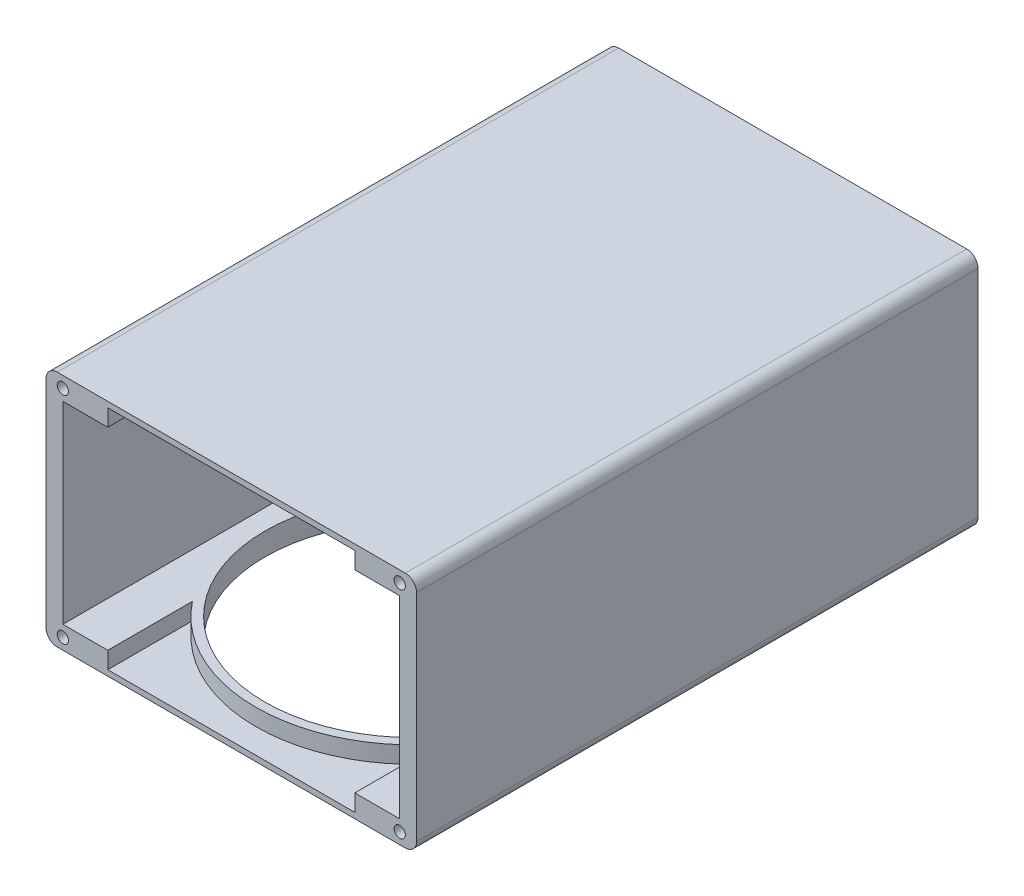
SolidWorks part; units mm, degrees
ref_plane "Front Plane" through (0, 0, 0) normal (0, 0, 1) x (1, 0, 0)
ref_plane "Top Plane" through (0, 0, 0) normal (0, 1, 0) x (1, 0, 0)
ref_plane "Right Plane" through (0, 0, 0) normal (1, 0, 0) x (0, 0, -1)
other "Configuration Table"
sketch "Sketch1" plane through (0, 0, 0) normal (0, 1, 0) x (1, 0, 0)
  line L1 (0, 0) -> (150, 0)
  line L2 (0, 0) -> (0, 160)
  line L3 (0, 160) -> (150, 160)
  line L4 (150, 0) -> (150, 160)
  dimension "D1" = 150
  dimension "D2" = 160
sketch "Sketch4" plane through (0, 0, 0) normal (0, 0, 1) x (1, 0, 0)
  line L0 (130, 86) -> (150, 86)
  line L1 (0, 0) -> (150, 0)
  line L2 (0, 0) -> (0, 86)
  line L3 (0, 86) -> (150, 86)
  line L4 (150, 0) -> (150, 86)
  line L5 (130, 93.5) -> (130, 86)
  line L6 (0, 0) -> (0, 20)
  line L7 (130, 25) -> (110, 25)
  line L8 (130, 25) -> (130, 50)
  line L9 (130, 50) -> (110, 50)
  line L10 (110, 25) -> (110, 50)
  line L11 (0, 20) -> (-5, 20)
  line L14 (20, -7.5) -> (20, 0)
  line L15 (20, 0) -> (0, 0)
  line L22 (0, 43) -> (150, 43) construction
  line L23 (75, 86) -> (75, 0) construction
  line L24 (20, 86) -> (0, 86)
  line L25 (20, 93.5) -> (20, 86)
  line L28 (0, 66) -> (-5, 66)
  line L29 (0, 86) -> (0, 66)
  line L32 (150, 66) -> (155, 66)
  line L33 (150, 86) -> (150, 66)
  line L34 (130, 0) -> (150, 0)
  line L35 (130, -7.5) -> (130, 0)
  line L38 (150, 20) -> (155, 20)
  line L39 (150, 0) -> (150, 20)
  line L40 (0, 86) -> (20, 86)
  line L41 (-7.5, -10) -> (-7.5, 0)
  line L43 (-7.5, 96) -> (157.5, 96)
  line L45 (157.5, -10) -> (-7.5, -10)
  line L46 (-5, 66) -> (-7.5, 66)
  line L47 (-5, 20) -> (-7.5, 20)
  line L48 (104.8793, 0) -> (-104.8793, 0) construction
  line L49 (20, -7.5) -> (130, -7.5)
  line L50 (155, 20) -> (157.5, 20)
  line L51 (0, 66) -> (0, 86)
  line L52 (155, 66) -> (157.5, 66)
  line L53 (20, 93.5) -> (130, 93.5)
  line L54 (-7.5, 66) -> (-7.5, 96)
  line L55 (157.5, 66) -> (157.5, 96)
  line L56 (157.5, 20) -> (157.5, -10)
  line L57 (-7.5, 20) -> (-7.5, 0)
  line L58 (130, 86) -> (150, 86)
  line L59 (150, 20) -> (150, 0)
  line L60 (0, 20) -> (0, 0)
  point P18 (0, 43)
  dimension "D1" = 150
  dimension "D2" = 86
  dimension "D5" = 25
  dimension "D6" = 20
  dimension "D7" = 20
  dimension "D8" = 5
  dimension "D11" = 106
  dimension "D12" = 165
sketch "Sketch5" plane through (0, 0, 0) normal (1, 0, 0) x (0, 0, -1)
  line L1 (0, 0) -> (160, 0)
  line L2 (0, 0) -> (0, 86)
  line L3 (0, 86) -> (160, 86)
  line L4 (160, 0) -> (160, 86)
  dimension "D1" = 160
  dimension "D2" = 86
extrude "Boss-Extrude3" add sketch "Sketch4" against normal blind 250 contours L52 L55 L43 L54 L46 L28 L2 L3 L25 L53 L5 L0 L4 L32 | L47 L57 L41 L45 L56 L50 L38 L4 L1 L35 L49 L14 L2 L11
fillet "Fillet1" radius 5 2 edges at (-7.5, 96, -125) (157.5, 96, -125)
fillet "Fillet2" radius 5 2 edges at (-7.5, -10, -125) (157.5, -10, -125)
sketch "Sketch7" plane through (0, 0, 0) normal (0, -1, 0) x (-1, 0, 0)
  line L0 (-150, 160) -> (-75, 160) construction
  line L1 (-150, 160) -> (0, 160) construction
  line L2 (-75, 160) -> (-75, 81) construction
  circle A0 centre (-75, 81) radius 66
  dimension "D2" = 132
  dimension "D1" = 79
extrude "Cut-Extrude1" cut sketch "Sketch7" along normal blind 10 contours A0
sketch "Sketch9" plane through (0, 0, 0) normal (0, -1, 0) x (1, 0, 0)
  line L0 (9, -81) -> (75, -81) construction
  circle A0 centre (75, -81) radius 66 construction
  circle A1 centre (75, -81) radius 70
  circle A2 centre (75, -81) radius 66
  dimension "D1" = 140
extrude "Boss-Extrude4" add sketch "Sketch9" along normal blind 8
sketch "Sketch14" plane through (0, 0, -250) normal (0, 0, -1) x (-1, 0, 0)
  line L0 (0, 86) -> (0, 91) construction
  line L1 (0, 106.7771) -> (0, -106.7771) construction
  line L2 (-150, 86) -> (-150, 43) construction
  line L3 (-150, 43) -> (0, 43) construction
  line L4 (0, 43) -> (0, 86) construction
  line L5 (0, 86) -> (-75, 86) construction
  line L6 (-75, 86) -> (-75, 0) construction
  circle A0 centre (0, 91) radius 2.5
  circle A1 centre (-150, 91) radius 2.5
  circle A2 centre (0, -5) radius 2.5
  circle A3 centre (-150, -5) radius 2.5
  dimension "D2" = 5
  dimension "D1" = 5
extrude "Cut-Extrude2" cut sketch "Sketch14" against normal blind 12
sketch "Sketch15" plane through (0, 0, 0) normal (0, 0, 1) x (1, 0, 0)
  line L0 (0, 86) -> (0, 91) construction
  line L1 (0, -106.7771) -> (0, 106.7771) construction
  line L2 (75, 86) -> (75, 0) construction
  line L3 (0, 43) -> (150, 43) construction
  circle A0 centre (0, 91) radius 2.5
  circle A1 centre (150, 91) radius 2.5
  circle A2 centre (150, -5) radius 2.5
  circle A3 centre (0, -5) radius 2.5
  dimension "D2" = 5
  dimension "D1" = 5
extrude "Cut-Extrude3" cut sketch "Sketch15" against normal blind 12 contours A0 | A3 | A2 | A1
sketch "Sketch17" plane through (0, 66, 0) normal (0, -1, 0) x (1, 0, 0)
  line L0 (0, -250) -> (0, 0) construction
  line L1 (-7.5, 0) -> (0, 0)
  line L2 (-7.5, 0) -> (-7.5, -250)
  line L3 (-7.5, -250) -> (0, -250)
  line L4 (0, 0) -> (0, -250)
  line L6 (150, 0) -> (157.5, 0)
  line L7 (150, 0) -> (150, -250)
  line L8 (150, -250) -> (157.5, -250)
  line L9 (157.5, 0) -> (157.5, -250)
extrude "Boss-Extrude5" add sketch "Sketch17" along normal blind 46
